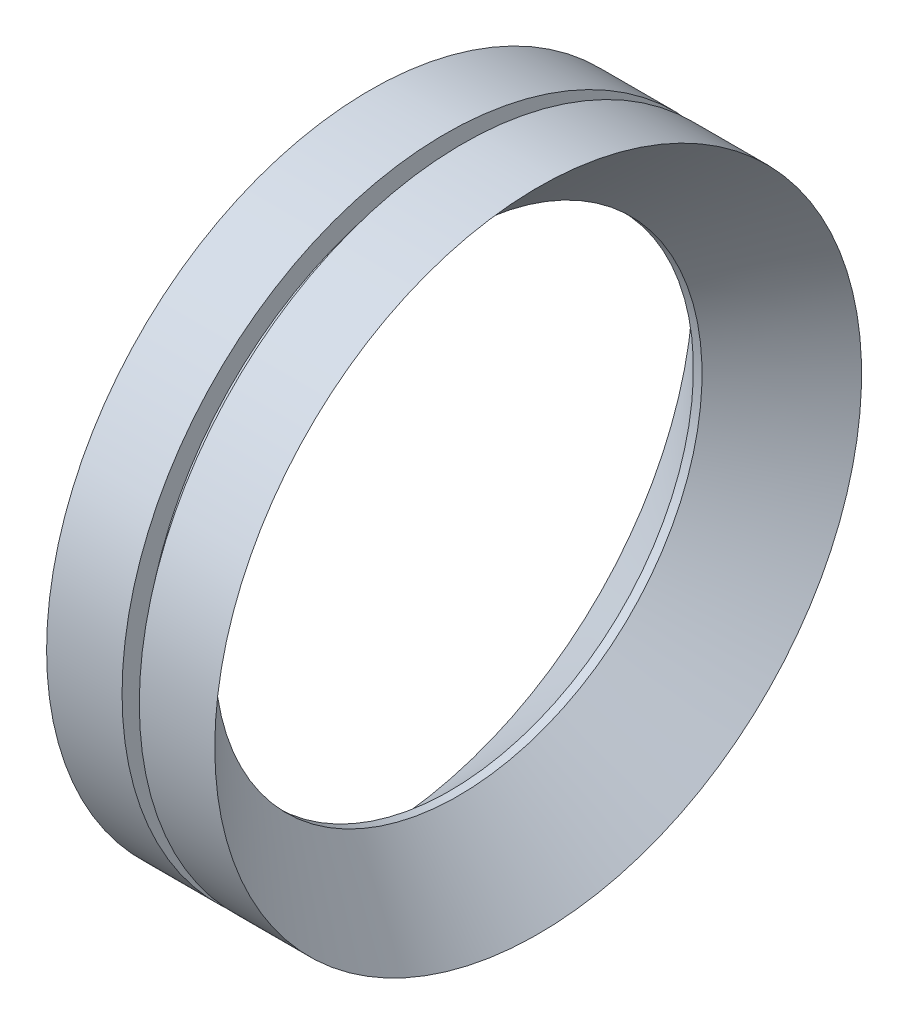
SolidWorks part; units mm, degrees
material "Резина"
ref_plane "Спереди" through (0, 0, 0) normal (0, 0, 1) x (1, 0, 0)
ref_plane "Сверху" through (0, 0, 0) normal (0, 1, 0) x (1, 0, 0)
ref_plane "Справа" through (0, 0, 0) normal (1, 0, 0) x (0, 0, -1)
sketch "Эскиз1" plane through (0, 0, 0) normal (0, 0, 1) x (1, 0, 0)
  line L0 (-128.4677, 0) -> (167.1774, 0) construction
  line L1 (-43, -150) -> (-8, -150)
  line L2 (-8, -150) -> (-8, -140)
  line L4 (0, -140) -> (0, -150)
  line L5 (0, -150) -> (35, -150)
  line L6 (35, -150) -> (-2, -113)
  line L8 (-6, -113) -> (-43, -150)
  line L9 (-6, -113) -> (-2, -113)
  line L10 (-8, -140) -> (0, -140)
  line L11 (-4, -140) -> (-4, -89.926) construction
  dimension "D1" = 78
  dimension "D2" = 226
  dimension "D3" = 90
  dimension "D4" = 300
  dimension "D5" = 280
  dimension "D6" = 8
revolve "Повернуть1" add sketch "Эскиз1" angle 360 about L0
